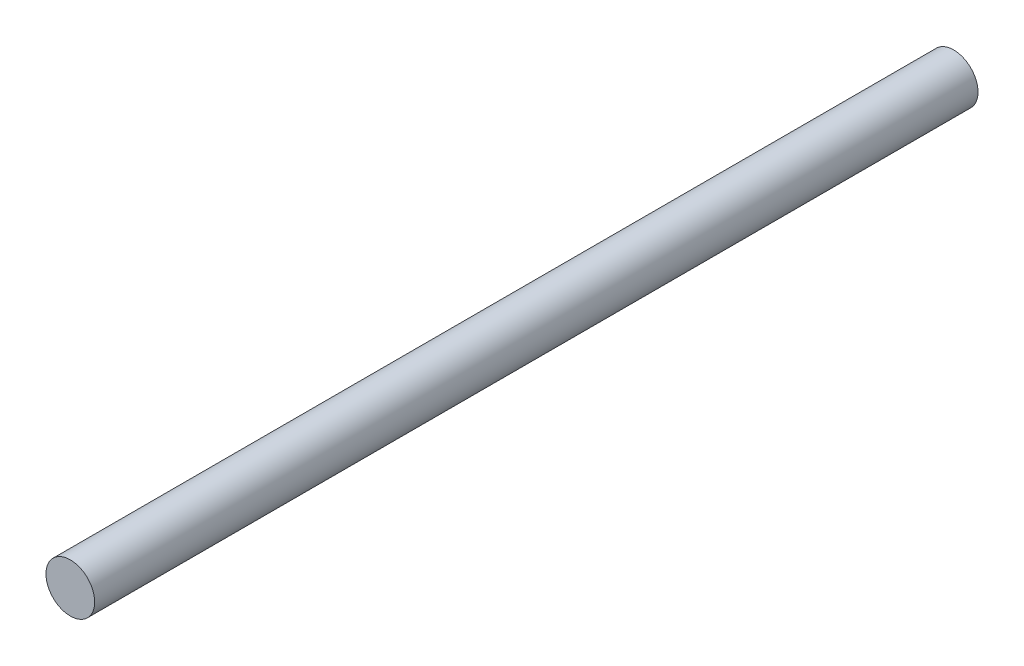
SolidWorks part; units mm, degrees
ref_plane "Front Plane" through (0, 0, 0) normal (0, 0, 1) x (1, 0, 0)
ref_plane "Top Plane" through (0, 0, 0) normal (0, 1, 0) x (1, 0, 0)
ref_plane "Right Plane" through (0, 0, 0) normal (1, 0, 0) x (0, 0, -1)
sketch "Sketch1" plane through (0, 0, 0) normal (0, 0, 1) x (1, 0, 0)
  circle A0 centre (0, 0) radius 4
  dimension "D1" = 8
extrude "Boss-Extrude1" add sketch "Sketch1" along normal mid plane 145
